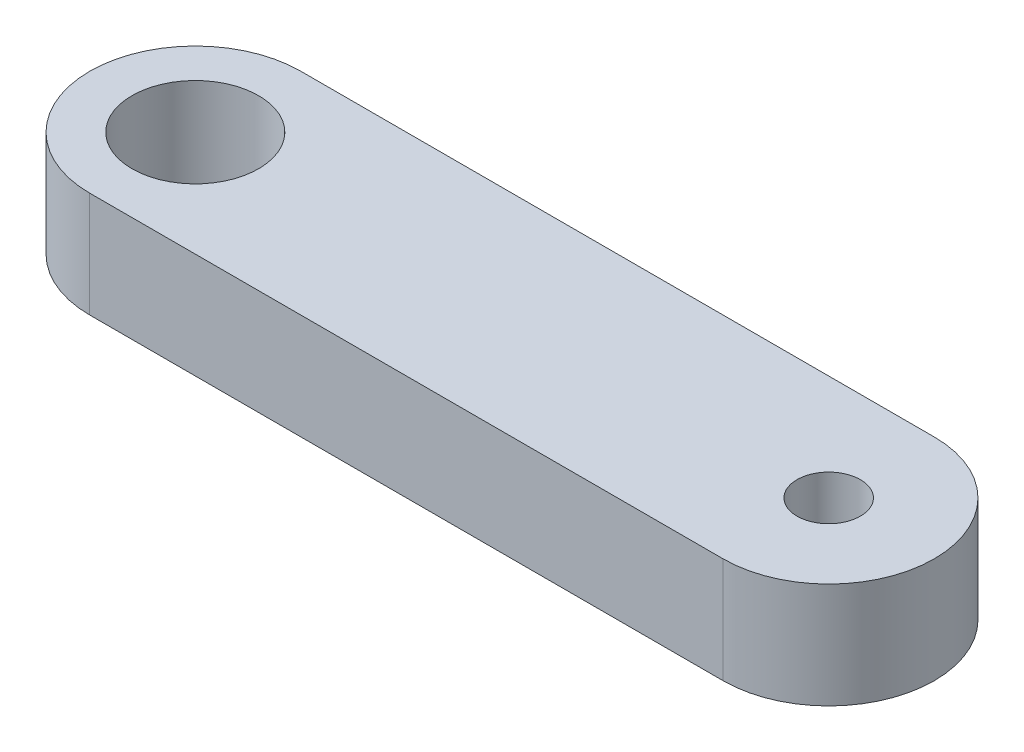
SolidWorks part; units mm, degrees
ref_plane "Front Plane" through (0, 0, 0) normal (0, 0, 1) x (1, 0, 0)
ref_plane "Top Plane" through (0, 0, 0) normal (0, 1, 0) x (1, 0, 0)
ref_plane "Right Plane" through (0, 0, 0) normal (1, 0, 0) x (0, 0, -1)
sketch "Sketch5" plane through (0, 0, 0) normal (0, 1, 0) x (1, 0, 0)
  line L0 (0, 0) -> (15, 0) construction
  line L1 (0, 2.5) -> (15, 2.5)
  line L2 (0, -2.5) -> (15, -2.5)
  line L3 (-2.5, 0) -> (17.5, 0) construction
  arc A0 (0, 2.5) -> (0, -2.5) centre (0, 0) ccw
  arc A1 (15, -2.5) -> (15, 2.5) centre (15, 0) ccw
  point P3 (7.5, 0)
  dimension "D1" = 20
  dimension "D2" = 5
extrude "Boss-Extrude2" add sketch "Sketch5" along normal blind 2.5
sketch "Sketch6" plane through (0, 2.5, 0) normal (0, 1, 0) x (1, 0, 0)
  circle A0 centre (0, 0) radius 1.5
  dimension "D1" = 3
extrude "Cut-Extrude2" cut sketch "Sketch6" against normal blind 2.5
sketch "Sketch7" plane through (0, 2.5, 0) normal (0, 1, 0) x (1, 0, 0)
  circle A0 centre (15, 0) radius 0.75
  dimension "D1" = 1.5
extrude "Cut-Extrude3" cut sketch "Sketch7" against normal blind 2.5
